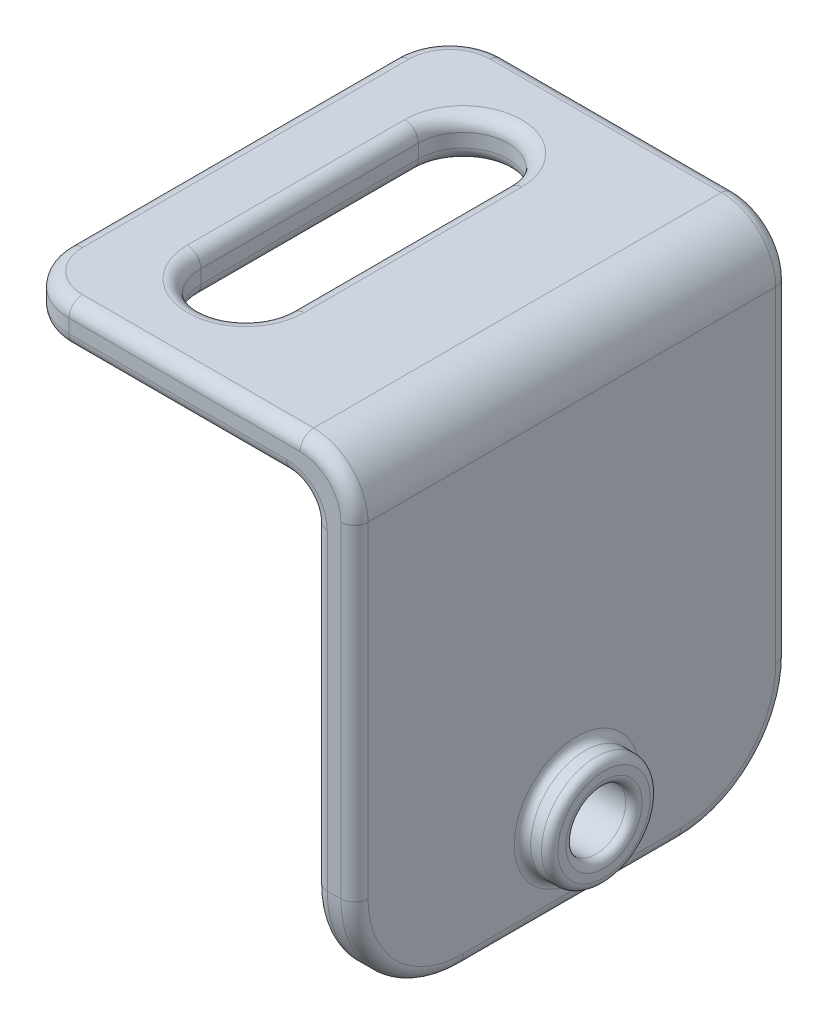
SolidWorks part; units mm, degrees
ref_plane "Front Plane" through (0, 0, 0) normal (0, 0, 1) x (1, 0, 0)
ref_plane "Top Plane" through (0, 0, 0) normal (0, 1, 0) x (1, 0, 0)
ref_plane "Right Plane" through (0, 0, 0) normal (1, 0, 0) x (0, 0, -1)
sketch "Sketch1" plane through (0, 0, 0) normal (0, 0, 1) x (1, 0, 0)
  line L0 (0, 0) -> (0, 18.053) construction
  line L1 (0, 0) -> (31.75, 0) construction
  line L2 (0, 0) -> (0, 3.81)
  line L3 (0, 3.81) -> (31.75, 3.81)
  line L4 (31.75, 3.81) -> (31.75, -41.91)
  line L5 (31.75, -41.91) -> (27.94, -41.91)
  line L6 (27.94, -41.91) -> (27.94, 0)
  line L7 (27.94, 0) -> (0, 0)
  dimension "D1" = 3.81
  dimension "D2" = 3.81
  dimension "D3" = 31.75
  dimension "D4" = 45.72
extrude "Boss-Extrude1" add sketch "Sketch1" along normal blind 40.64
sketch "Sketch2" plane through (0, 3.81, 0) normal (0, 1, 0) x (1, 0, 0)
  line L0 (11.43, 0) -> (11.43, -40.64) construction
  line L1 (31.75, 0) -> (0, 0) construction
  line L2 (31.75, -40.64) -> (0, -40.64) construction
  line L3 (11.43, -10.16) -> (11.43, -30.48) construction
  line L4 (15.621, -10.16) -> (15.621, -30.48)
  line L5 (7.239, -10.16) -> (7.239, -30.48)
  line L6 (0, -40.64) -> (0, 0) construction
  arc A0 (15.621, -10.16) -> (7.239, -10.16) centre (11.43, -10.16) ccw
  arc A1 (7.239, -30.48) -> (15.621, -30.48) centre (11.43, -30.48) ccw
  point P8 (11.43, -20.32)
  dimension "D1" = 20.32
  dimension "D2" = 8.382
  dimension "D3" = 11.43
extrude "Cut-Extrude1" cut sketch "Sketch2" against normal through all
fillet "Fillet1" radius 10.16 2 edges at (29.845, -41.91, 0) (29.845, -41.91, 40.64)
fillet "Fillet2" radius 2.54 1 edges at (27.94, 0, 20.32)
fillet "Fillet3" radius 5.08 2 edges at (0, 1.905, 40.64) (0, 1.905, 0)
fillet "Fillet4" radius 5.08 1 edges at (31.75, 3.81, 20.32)
fillet "Fillet8" radius 1.27 8 edges at (11.43, 0, 34.671) (11.43, 0, 5.969) (11.43, 3.81, 34.671) (11.43, 3.81, 5.969) (7.239, 0, 20.32) (7.239, 3.81, 20.32) (15.621, 0, 20.32) (15.621, 3.81, 20.32)
fillet "Fillet9" radius 1.27 24 edges at (1.4879, 0, 39.1521) (0, 0, 20.32) (1.4879, 0, 1.4879) (15.24, 0, 0) (27.1961, -0.7439, 0) (27.94, -17.145, 0) (27.94, -38.9342, 2.9758) (27.94, -41.91, 20.32) (27.94, -38.9342, 37.6642) (27.94, -17.145, 40.64) (27.1961, -0.7439, 40.64) (30.2621, 2.3221, 40.64) (31.75, -16.51, 40.64) (31.75, -38.9342, 37.6642) (31.75, -41.91, 20.32) (31.75, -38.9342, 2.9758) (31.75, -16.51, 0) (30.2621, 2.3221, 0) (15.875, 3.81, 0) (1.4879, 3.81, 1.4879) (0, 3.81, 20.32) (1.4879, 3.81, 39.1521) (15.24, 0, 40.64) (15.875, 3.81, 40.64)
sketch "Sketch10" plane through (31.75, 0, 0) normal (1, 0, 0) x (0, 0, -1)
  line L0 (-20.32, 3.81) -> (-19.7646, -41.8733) construction
  line L1 (-39.37, 3.81) -> (-1.27, 3.81) construction
  line L2 (-19.7646, -41.8733) -> (-19.8577, -34.2127) construction
  circle A1 centre (-19.8577, -34.2127) radius 5.08
extrude "Boss-Extrude2" add sketch "Sketch10" along normal blind 2.54 contours A1
sketch "Sketch11" plane through (34.29, 0, 0) normal (1, 0, 0) x (0, 0, -1)
  circle A0 centre (-19.8577, -34.2127) radius 2.794
extrude "Cut-Extrude4" cut sketch "Sketch11" against normal through all
fillet "Fillet10" radius 0.762 3 edges at (34.29, -31.4187, 19.8577) (31.75, -39.2927, 19.8577) (34.29, -29.1327, 19.8577)
